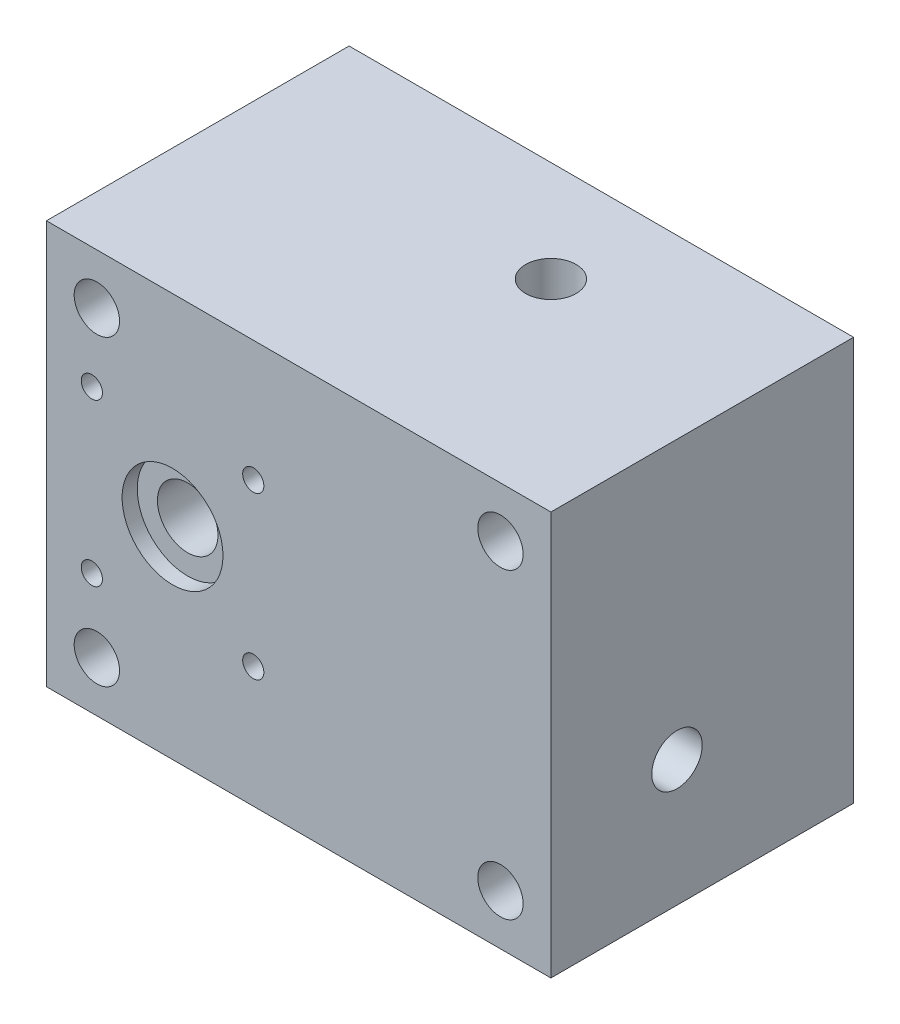
SolidWorks part; units mm, degrees
ref_plane "前视基准面" through (0, 0, 0) normal (0, 0, 1) x (1, 0, 0)
ref_plane "上视基准面" through (0, 0, 0) normal (0, 1, 0) x (1, 0, 0)
ref_plane "右视基准面" through (0, 0, 0) normal (1, 0, 0) x (0, 0, -1)
sketch "草图1" plane through (0, 0, 0) normal (0, 0, 1) x (1, 0, 0)
  line L0 (-50, -40) -> (50, -40)
  line L1 (50, -40) -> (50, 40)
  line L2 (50, 40) -> (-50, 40)
  line L3 (-50, 40) -> (-50, -40)
extrude "凸台-拉伸1" add sketch "草图1" along normal blind 60
ref_plane "基准面1" through (0, 0, 60) normal (0, 0, 1) x (1, 0, 0)
sketch "草图2" plane through (0, 0, 60) normal (0, 0, 1) x (1, 0, 0)
  circle A0 centre (-25, 0) radius 10
extrude "切除-拉伸1" cut sketch "草图2" against normal blind 3
sketch "草图3" plane through (0, 0, 60) normal (0, 0, 1) x (1, 0, 0)
  circle A0 centre (-25, 0) radius 6
extrude "切除-拉伸2" cut sketch "草图3" against normal blind 40
ref_plane "基准面2" through (-50, 0, 0) normal (1, 0, 0) x (0, 0, -1)
sketch "草图4" plane through (-50, 0, 0) normal (1, 0, 0) x (0, 0, -1)
  circle A0 centre (-20, 0) radius 8
extrude "切除-拉伸3" cut sketch "草图4" along normal blind 8
sketch "草图5" plane through (-50, 0, 0) normal (1, 0, 0) x (0, 0, -1)
  circle A0 centre (-20, 0) radius 5
extrude "切除-拉伸4" cut sketch "草图5" along normal blind 70
ref_plane "基准面3" through (0, 40, 0) normal (0, 1, 0) x (1, 0, 0)
sketch "草图6" plane through (0, 40, 0) normal (0, 1, 0) x (1, 0, 0)
  circle A0 centre (10, -20) radius 5
extrude "切除-拉伸5" cut sketch "草图6" against normal blind 40
sketch "草图7" plane through (0, 0, 0) normal (0, 0, 1) x (1, 0, 0)
  circle A0 centre (25, -15) radius 7
extrude "切除-拉伸6" cut sketch "草图7" along normal blind 45
ref_plane "基准面4" through (50, 0, 0) normal (1, 0, 0) x (0, 0, -1)
sketch "草图8" plane through (50, 0, 0) normal (1, 0, 0) x (0, 0, -1)
  circle A0 centre (-35, -15) radius 5
extrude "切除-拉伸7" cut sketch "草图8" against normal blind 30
sketch "草图9" plane through (0, 0, 0) normal (0, 0, 1) x (1, 0, 0)
  circle A0 centre (40, 30) radius 4.5
  circle A1 centre (40, -30) radius 4.5
  circle A2 centre (-40, 30) radius 4.5
  circle A3 centre (-40, -30) radius 4.5
extrude "切除-拉伸8" cut sketch "草图9" against normal mid plane 202
sketch "草图10" plane through (0, 0, 60) normal (0, 0, 1) x (1, 0, 0)
  circle A0 centre (-9, 16) radius 2.1
  circle A1 centre (-9, -16) radius 2.1
  circle A2 centre (-41, 16) radius 2.1
  circle A3 centre (-41, -16) radius 2.1
extrude "切除-拉伸9" cut sketch "草图10" against normal blind 10
